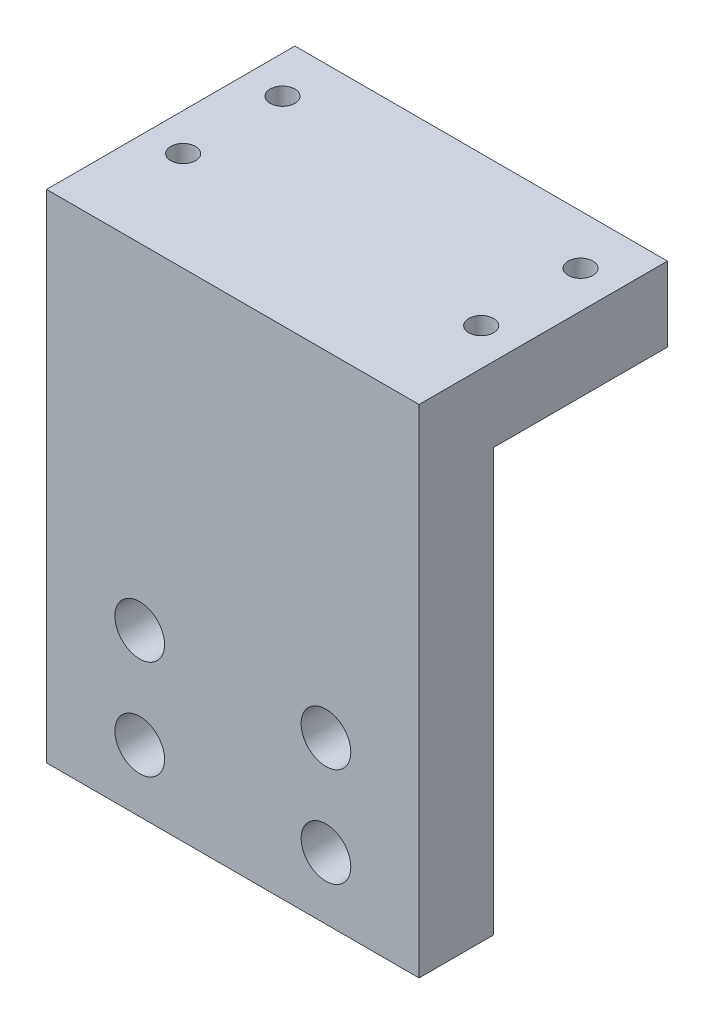
SolidWorks part; units mm, degrees
ref_plane "Front Plane" through (0, 0, 0) normal (0, 0, 1) x (1, 0, 0)
ref_plane "Top Plane" through (0, 0, 0) normal (0, 1, 0) x (1, 0, 0)
ref_plane "Right Plane" through (0, 0, 0) normal (1, 0, 0) x (0, 0, -1)
sketch "Sketch1" plane through (0, 0, 0) normal (1, 0, 0) x (0, 0, -1)
  line L0 (7.3621, -50) -> (7.3621, 150)
  line L1 (7.3621, 150) -> (107.3621, 150)
  line L2 (7.3621, -50) -> (37.3621, -50)
  line L3 (37.3621, -50) -> (37.3621, 120)
  line L4 (37.3621, 120) -> (107.3621, 120)
  line L5 (107.3621, 120) -> (107.3621, 150)
  dimension "D1" = 200
  dimension "D2" = 100
  dimension "D3" = 30
  dimension "D4" = 30
extrude "Boss-Extrude1" add sketch "Sketch1" along normal blind 150
sketch "Sketch2" plane through (0, 0, -7.3621) normal (0, 0, 1) x (1, 0, 0)
  line L0 (150, -50) -> (0, -50) construction
  line L1 (0, 150) -> (0, -50) construction
  line L2 (75, 150) -> (75, -50) construction
  line L3 (150, 150) -> (0, 150) construction
  circle A0 centre (37.5, -25) radius 10
  circle A1 centre (37.5, 15) radius 10
  circle A2 centre (112.5, -25) radius 10
  circle A3 centre (112.5, 15) radius 10
  dimension "D1" = 20
  dimension "D3" = 20
  dimension "D2" = 25
  dimension "D4" = 40
  dimension "D5" = 37.5
  dimension "D6" = 37.5
extrude "Cut-Extrude1" cut sketch "Sketch2" against normal blind 150
sketch "Sketch3" plane through (0, 150, 0) normal (0, 1, 0) x (1, 0, 0)
  line L0 (150, 107.3621) -> (0, 107.3621) construction
  line L2 (0, 107.3621) -> (0, 7.3621) construction
  circle A0 centre (15, 87.3621) radius 5
  circle A1 centre (15, 47.3621) radius 5
  circle A2 centre (135, 47.3621) radius 5
  circle A3 centre (135, 87.3621) radius 5
  dimension "D1" = 15
  dimension "D2" = 10
  dimension "D3" = 10
  dimension "D4" = 10
  dimension "D5" = 10
  dimension "D6" = 40
  dimension "D7" = 40
  dimension "D8" = 20
  dimension "D9" = 120
extrude "Cut-Extrude2" cut sketch "Sketch3" against normal through all
